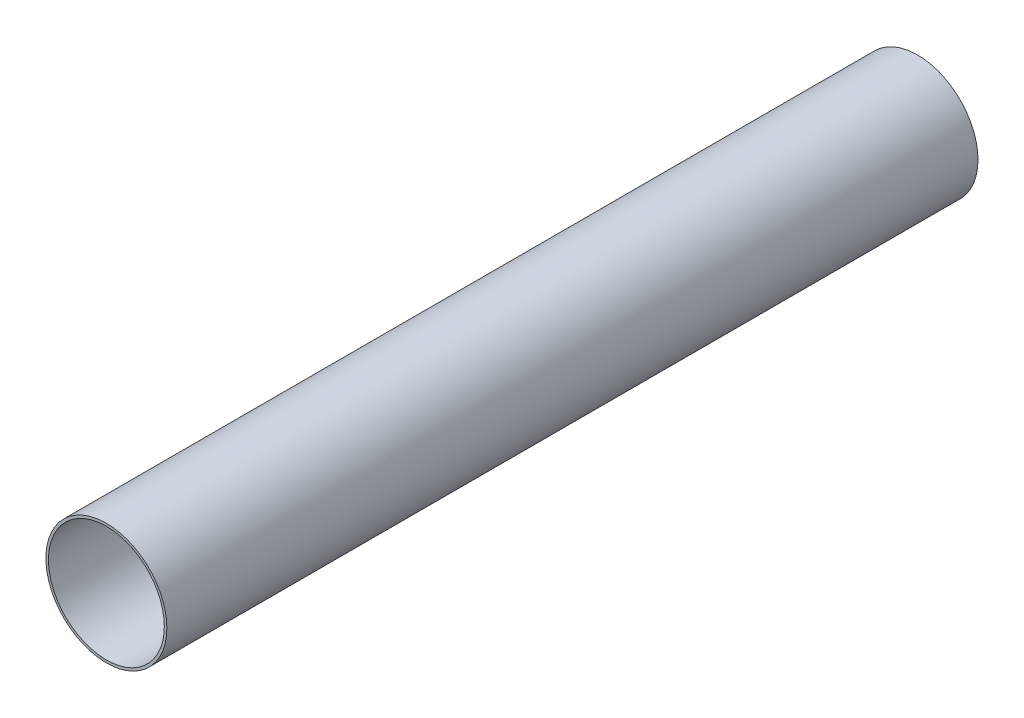
SolidWorks part; units mm, degrees
material "Silicon Rubber"
ref_plane "Front Plane" through (0, 0, 0) normal (0, 0, 1) x (1, 0, 0)
ref_plane "Top Plane" through (0, 0, 0) normal (0, 1, 0) x (1, 0, 0)
ref_plane "Right Plane" through (0, 0, 0) normal (1, 0, 0) x (0, 0, -1)
sketch "Sketch1" plane through (0, 0, 0) normal (0, 0, 1) x (1, 0, 0)
  circle A0 centre (0, 0) radius 26.5165
  circle A1 centre (0, 0) radius 25.4
  dimension "D1" = 53.033
  dimension "D2" = 50.8
extrude "Boss-Extrude1" add sketch "Sketch1" along normal mid plane 355.6
equation "\"D1@Sketch1\"=sqr(1.5^2-1.375^2+4)"
